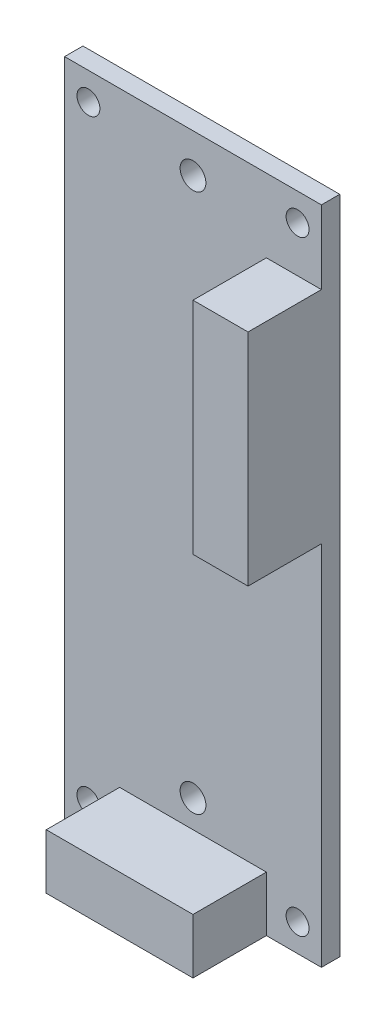
SolidWorks part; units mm, degrees
material "Printed Circuit Board"
ref_plane "Front Plane" through (0, 0, 0) normal (0, 0, 1) x (1, 0, 0)
ref_plane "Top Plane" through (0, 0, 0) normal (0, 1, 0) x (1, 0, 0)
ref_plane "Right Plane" through (0, 0, 0) normal (1, 0, 0) x (0, 0, -1)
sketch "Sketch1" plane through (0, 0, 0) normal (0, 0, 1) x (1, 0, 0)
  line L1 (-17.78, -45.72) -> (17.78, -45.72)
  line L2 (-17.78, -45.72) -> (-17.78, 45.72)
  line L3 (-17.78, 45.72) -> (17.78, 45.72)
  line L4 (17.78, -45.72) -> (17.78, 45.72)
  line L5 (-17.78, -45.72) -> (17.78, 45.72) construction
  line L6 (-17.78, 45.72) -> (17.78, -45.72) construction
  point P0 (0, 0)
  dimension "D1" = 91.44
  dimension "D2" = 35.56
extrude "Extrude1" add sketch "Sketch1" along normal blind 2.54
sketch "Sketch2" plane through (0, 0, 2.54) normal (0, 0, 1) x (1, 0, 0)
  line L0 (0, 45.72) -> (0, 41.91) construction
  line L1 (17.78, 45.72) -> (-17.78, 45.72) construction
  line L2 (0, 41.91) -> (14.478, 41.91) construction
  dimension "D1" = 3.81
  dimension "D2" = 14.478
hole_wizard "1/8 (0.125) Diameter Hole1" positions "3DSketch1" profile "Sketch3" hole size "1/8" standard "Ansi Inch"
sketch3d "3DSketch1"
  point P0 (14.478, 41.91, 2.54)
sketch "Sketch3" plane through (14.478, 41.91, 2.54) normal (1, 0, 0) x (0, -1, 0)
  line L0 (0, 0) -> (0, 16.1939)
  line L1 (0, 16.1939) -> (1.5875, 15.24)
  line L2 (1.5875, 15.24) -> (1.5875, 0)
  line L5 (1.5875, 0) -> (0, 0)
  line L10 (0, 16.1939) -> (-1.5875, 15.24) construction
  line L11 (0, -6.35) -> (0, 107.95) construction
  dimension "Hole Dia." = 3.175
  dimension "Hole Depth" = 15.24
  dimension "Drill Angle" = 118
mirror "Mirror1" about plane through (0, 0, 0) normal (1, 0, 0) of "1/8 (0.125) Diameter Hole1"
mirror "Mirror2" about plane through (0, 0, 0) normal (0, 1, 0) of "Mirror1", "1/8 (0.125) Diameter Hole1"
sketch "Sketch4" plane through (0, 0, 2.54) normal (0, 0, 1) x (1, 0, 0)
  line L0 (0, -45.72) -> (0, -34.29) construction
  line L1 (-17.78, -45.72) -> (17.78, -45.72) construction
  line L2 (0, -34.29) -> (0, 41.148) construction
  dimension "D1" = 11.43
  dimension "D2" = 75.438
hole_wizard "#28 (0.1405) Diameter Hole1" positions "3DSketch2" profile "Sketch5" hole size "#28" standard "Ansi Inch"
sketch3d "3DSketch2"
  line L0 (0, -34.29, 2.54) -> (0, 41.148, 2.54) construction
  point P0 (0, -34.29, 2.54)
  point P3 (0, 40.3499, 2.54)
sketch "Sketch5" plane through (0, -34.29, 2.54) normal (1, 0, 0) x (0, -1, 0)
  line L0 (0, 0) -> (0, 16.3121)
  line L1 (0, 16.3121) -> (1.7843, 15.24)
  line L2 (1.7843, 15.24) -> (1.7843, 0)
  line L5 (1.7843, 0) -> (0, 0)
  line L10 (0, 16.3121) -> (-1.7844, 15.24) construction
  line L11 (0, -6.35) -> (0, 107.95) construction
  dimension "Hole Dia." = 3.5687
  dimension "Hole Depth" = 15.24
  dimension "Drill Angle" = 118
sketch "Sketch6" plane through (0, 0, 2.54) normal (0, 0, 1) x (1, 0, 0)
  line L0 (0, -45.72) -> (10.16, -45.72)
  line L1 (-17.78, -45.72) -> (17.78, -45.72) construction
  line L2 (10.16, -45.72) -> (10.16, -38.1)
  line L3 (10.16, -38.1) -> (-10.16, -38.1)
  line L4 (-10.16, -38.1) -> (-10.16, -45.72)
  line L5 (-10.16, -45.72) -> (0, -45.72)
  dimension "D1" = 20.32
  dimension "D2" = 7.62
extrude "Extrude2" add sketch "Sketch6" along normal blind 10.16
sketch "Sketch7" plane through (0, 0, 2.54) normal (0, 0, 1) x (1, 0, 0)
  line L0 (17.78, 45.72) -> (17.78, 35.56) construction
  line L1 (17.78, -45.72) -> (17.78, 45.72) construction
  line L2 (17.78, 35.56) -> (10.16, 35.56)
  line L3 (10.16, 35.56) -> (10.16, 5.08)
  line L4 (10.16, 5.08) -> (17.78, 5.08)
  line L5 (17.78, 5.08) -> (17.78, 35.56)
  dimension "D1" = 30.48
  dimension "D2" = 10.16
  dimension "D3" = 7.62
extrude "Extrude3" add sketch "Sketch7" along normal blind 10.16
